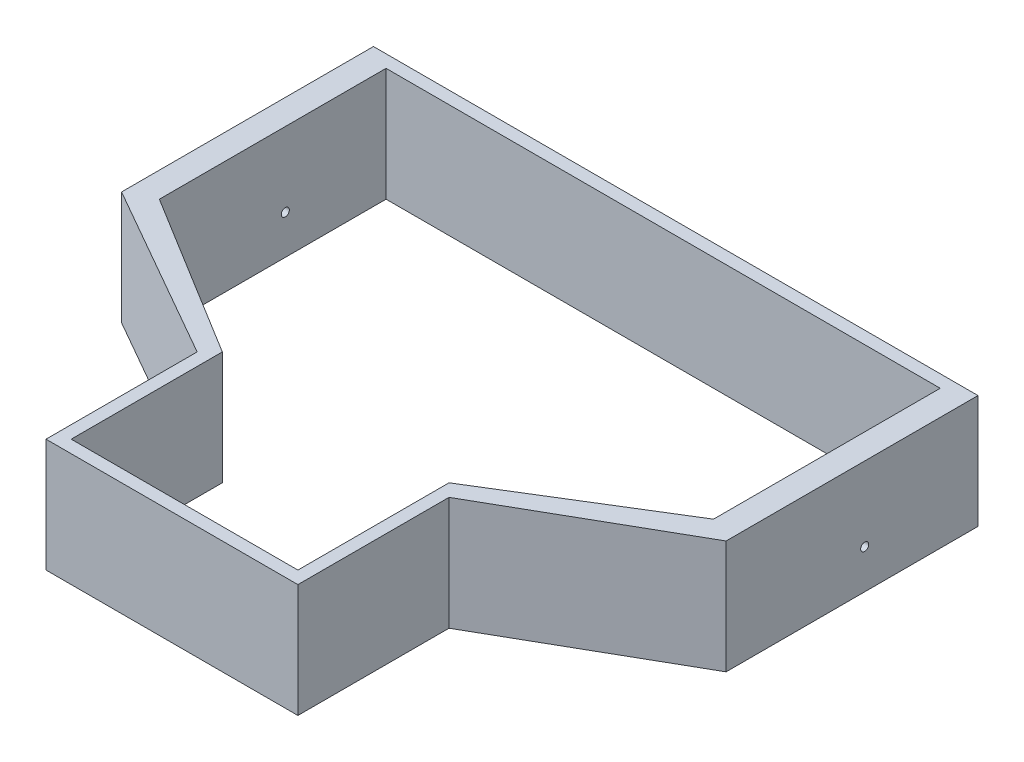
SolidWorks part; units mm, degrees
ref_plane "Front Plane" through (0, 0, 0) normal (0, 0, 1) x (1, 0, 0)
ref_plane "Top Plane" through (0, 0, 0) normal (0, 1, 0) x (1, 0, 0)
ref_plane "Right Plane" through (0, 0, 0) normal (1, 0, 0) x (0, 0, -1)
sketch "Sketch1" plane through (0, 0, 0) normal (0, 1, 0) x (1, 0, 0)
  line L0 (-152.4, 0) -> (152.4, 0)
  line L1 (-152.4, 0) -> (-152.4, -127)
  line L2 (-152.4, -127) -> (-63.5, -177.8)
  line L3 (-63.5, -177.8) -> (-63.5, -254)
  line L4 (-63.5, -254) -> (63.5, -254)
  line L5 (63.5, -254) -> (63.5, -177.8)
  line L6 (63.5, -177.8) -> (152.4, -127)
  line L7 (152.4, -127) -> (152.4, 0)
  point P3 (-63.5, -251.72)
  point P4 (0, 0)
  point P9 (63.5, -175.3294)
  point P12 (0, 0)
  point P13 (0, 0)
  dimension "D1" = 304.8
  dimension "D2" = 127
  dimension "D3" = 88.9
  dimension "D4" = 88.9
  dimension "D5" = 76.2
  dimension "D6" = 50.8
extrude "Boss-Extrude1" add sketch "Sketch1" along normal blind 57.15
sketch "Sketch2" plane through (0, 57.15, 0) normal (0, 1, 0) x (1, 0, 0)
  line L0 (-139.7, -6.35) -> (139.7, -6.35)
  line L1 (-139.7, -6.35) -> (-139.7, -120.65)
  line L2 (-139.7, -120.65) -> (-57.15, -171.45)
  line L3 (-57.15, -171.45) -> (-57.15, -247.65)
  line L4 (-57.15, -247.65) -> (57.15, -247.65)
  line L5 (57.15, -247.65) -> (57.15, -171.45)
  line L6 (57.15, -171.45) -> (139.7, -120.65)
  line L7 (139.7, -120.65) -> (139.7, -6.35)
  line L8 (-152.4, 0) -> (-152.4, -127) construction
  line L9 (-63.5, -177.8) -> (-63.5, -254) construction
  line L10 (63.5, -254) -> (63.5, -177.8) construction
  line L11 (-63.5, -254) -> (63.5, -254) construction
  point P3 (0, -6.35)
  point P7 (0, 0)
  point P19 (0, 0)
  point P20 (0, 0)
  point P21 (0, 0)
  point P22 (0, 0)
  point P23 (-57.15, -168.867)
  dimension "D1" = 6.35
  dimension "D2" = 279.4
  dimension "D3" = 12.7
  dimension "D4" = 6.35
  dimension "D5" = 6.35
  dimension "D6" = 6.35
  dimension "D7" = 50.8
  dimension "D8" = 50.8
  dimension "D9" = 76.2
extrude "Cut-Extrude1" cut sketch "Sketch2" against normal up to surface (57.15 mm away) up to face at (0, 0, 139.7)
sketch "Sketch3" plane through (152.4, 0, 0) normal (1, 0, 0) x (0, 0, -1)
  line L2 (-127, 57.15) -> (0, 57.15) construction
  circle A0 centre (-57.15, 19.685) radius 2.032
  dimension "D1" = 4.064
  dimension "D2" = 57.15
  dimension "D3" = 37.465
extrude "Cut-Extrude2" cut sketch "Sketch3" against normal through all
